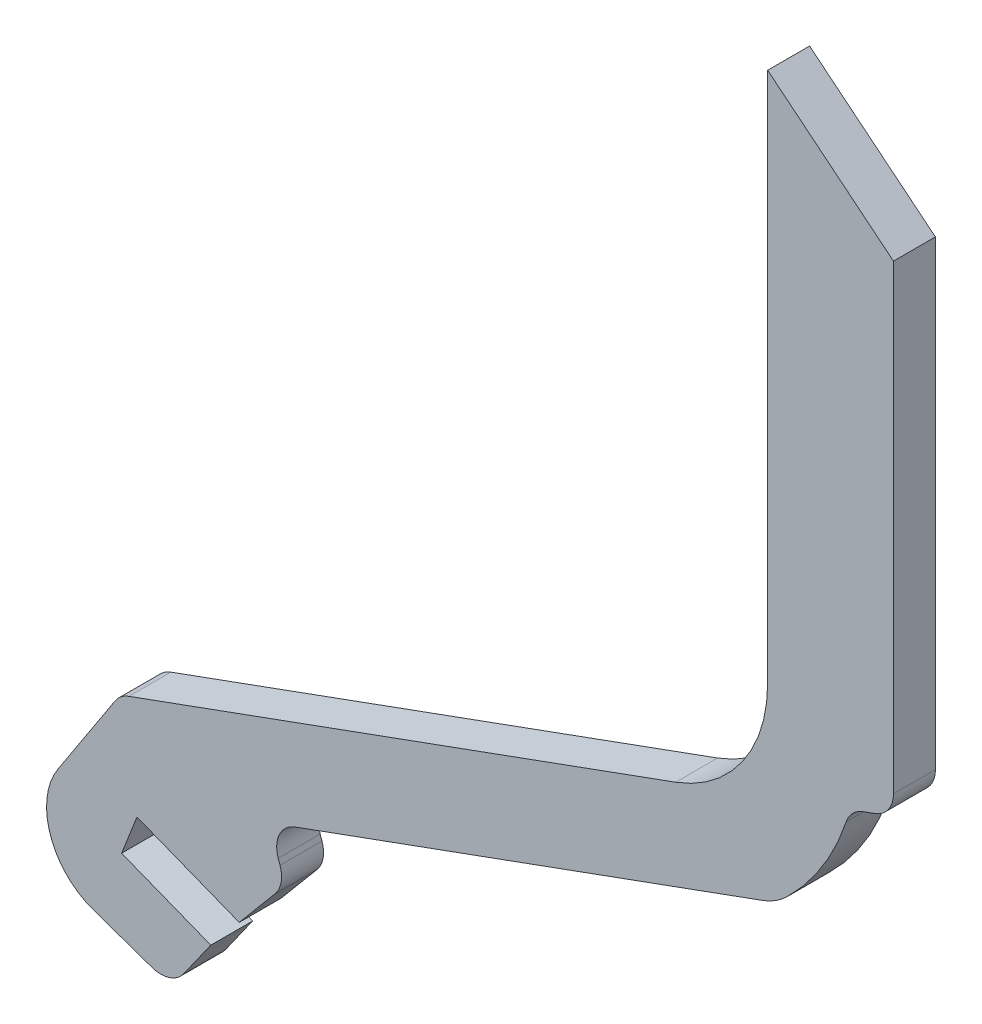
SolidWorks part; units mm, degrees
ref_plane "Front" through (0, 0, 0) normal (0, 0, 1) x (1, 0, 0)
ref_plane "Top" through (0, 0, 0) normal (0, 1, 0) x (1, 0, 0)
ref_plane "Right" through (0, 0, 0) normal (1, 0, 0) x (0, 0, -1)
sketch "Sketch1" plane through (0, 0, 0) normal (0, 0, 1) x (1, 0, 0)
  line L0 (732.0343, -38.7015) -> (738.4127, -41.2067)
  line L1 (732.552, -28.7232) -> (771.6653, -14.4871)
  line L2 (785.0694, -9.6084) -> (785.9291, -9.2955)
  line L3 (787.2451, 25.5839) -> (787.2451, -7.4161)
  line L4 (778.2451, -5.0902) -> (778.2451, 32.9098)
  line L8 (777.8755, -18.7051) -> (744.4405, -30.8745)
  line L10 (738.4127, -41.2067) -> (736.4734, -43.9477)
  line L13 (734.18, -44.6803) -> (730.0133, -43.2219)
  line L20 (740.4452, -38.7819) -> (733.131, -35.9092)
  line L21 (733.131, -35.9092) -> (732.0343, -38.7015)
  line L24 (727.4771, -35.7712) -> (731.5609, -29.51)
  line L26 (743.0088, -35.7267) -> (740.4452, -38.7819)
  line L27 (743.2361, -33.4127) -> (743.3651, -33.7823)
  line L76 (778.2451, 32.9098) -> (787.2451, 25.5839)
  arc A0 (779.6098, -17.6188) -> (783.8554, -10.8572) centre (767.9146, -5.5615) ccw
  arc A1 (777.8755, -18.7051) -> (779.6098, -17.6188) centre (776.201, -14.1045) ccw
  arc A2 (771.6653, -14.4871) -> (778.2451, -5.0902) centre (768.2451, -5.0902) ccw
  arc A3 (730.0133, -43.2219) -> (727.4771, -35.7712) centre (731.6651, -38.5027) cw
  arc A4 (731.5609, -29.51) -> (732.552, -28.7232) centre (733.236, -30.6026) cw
  arc A5 (743.0088, -35.7267) -> (743.3651, -33.7823) centre (741.4767, -34.4411) ccw
  arc A6 (734.18, -44.6803) -> (736.4734, -43.9477) centre (734.8407, -42.7926) ccw
  arc A7 (783.8554, -10.8572) -> (785.0694, -9.6084) centre (785.7534, -11.4878) cw
  arc A8 (785.9291, -9.2955) -> (787.2451, -7.4161) centre (785.2451, -7.4161) ccw
  arc A9 (743.2361, -33.4127) -> (744.4405, -30.8745) centre (745.1245, -32.7539) cw
  point P24 (784.1284, -9.9509)
  dimension "D4" = 10
  dimension "D5" = 2
  dimension "D6" = 2
  dimension "D10" = 5
  dimension "D1" = 3
  dimension "D2" = 90
  dimension "D3" = 110
  dimension "D7" = 7.8581
  dimension "D8" = 6.8527
  dimension "D9" = 150
  dimension "D11" = 38
  dimension "D12" = 33
  dimension "D13" = 9
extrude "Base-Extrude" add sketch "Sketch1" along normal blind 3
